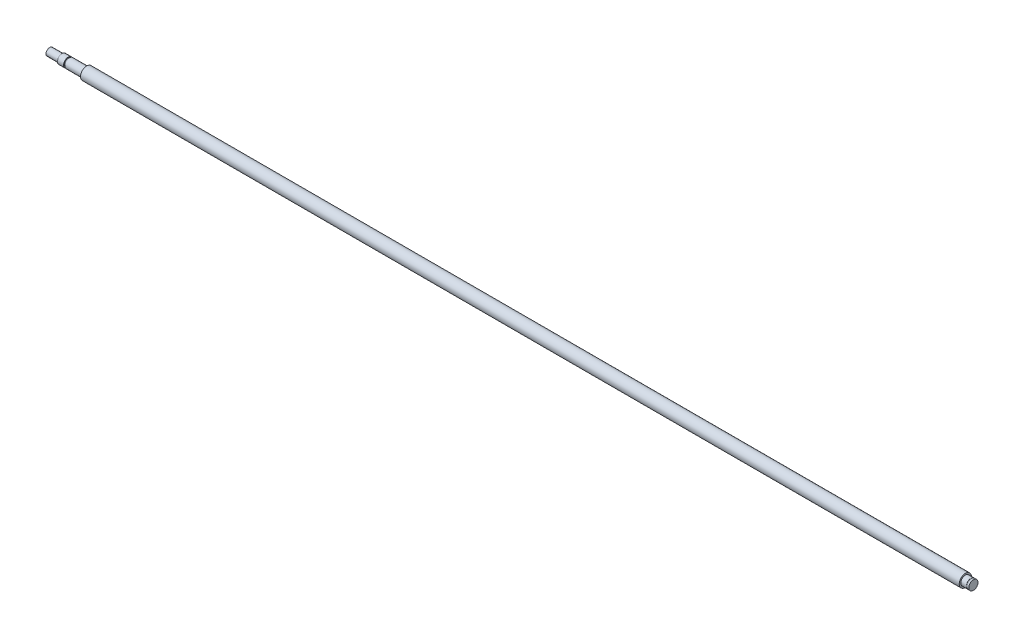
SolidWorks part; units mm, degrees
material "Plain Carbon Steel"
ref_plane "Front Plane" through (0, 0, 0) normal (0, 0, 1) x (1, 0, 0)
ref_plane "Top Plane" through (0, 0, 0) normal (0, 1, 0) x (1, 0, 0)
ref_plane "Right Plane" through (0, 0, 0) normal (1, 0, 0) x (0, 0, -1)
sketch "Sketch1" plane through (0, 0, 0) normal (0, 0, 1) x (1, 0, 0)
  line L0 (-60, 0) -> (1440, 0)
  line L1 (1440, 0) -> (1440, 7.5)
  line L2 (1440, 7.5) -> (1437.15, 7.5)
  line L3 (1437.15, 7.5) -> (1437.15, 7.15)
  line L4 (1437.15, 7.15) -> (1436, 7.15)
  line L5 (1436, 7.15) -> (1436, 7.5)
  line L6 (1436, 7.5) -> (1427, 7.5)
  line L7 (1427, 7.5) -> (1427, 10)
  line L8 (1427, 10) -> (0, 10)
  line L9 (0, 10) -> (0, 7.5)
  line L10 (0, 7.5) -> (-28, 7.5)
  line L11 (-28, 7.5) -> (-28, 6)
  line L12 (-28, 6) -> (-30, 6)
  line L13 (-30, 6) -> (-30, 7.5)
  line L14 (-30, 7.5) -> (-40, 7.5)
  line L15 (-40, 7.5) -> (-40, 6)
  line L16 (-40, 6) -> (-60, 6)
  line L17 (-60, 6) -> (-60, 0)
  point P18 (713.5, 10)
  dimension "D1" = 2
  dimension "D2" = 20
  dimension "D3" = 12
  dimension "D4" = 40
  dimension "D5" = 1.15
  dimension "D6" = 0.35
  dimension "D7" = 9
  dimension "D8" = 13
  dimension "D9" = 1500
  dimension "D10" = 6
  dimension "D11" = 7.5
  dimension "D12" = 10
revolve "Revolve1" add sketch "Sketch1" angle 360 about L0
